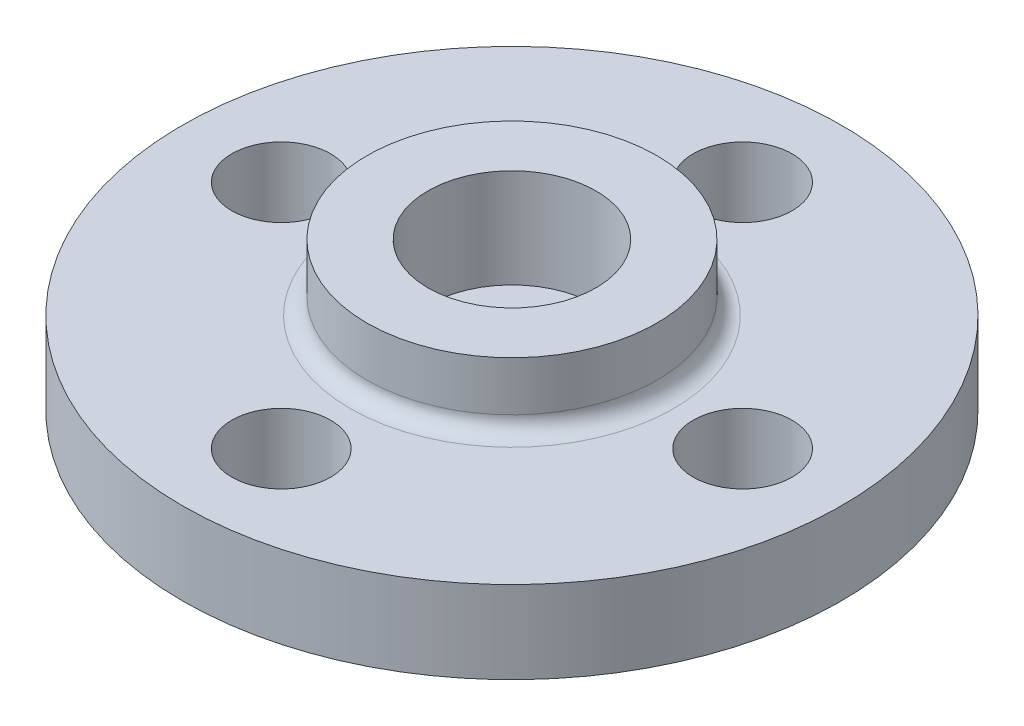
SolidWorks part; units mm, degrees
ref_plane "前视基准面" through (0, 0, 0) normal (0, 0, 1) x (1, 0, 0)
ref_plane "上视基准面" through (0, 0, 0) normal (0, 1, 0) x (1, 0, 0)
ref_plane "右视基准面" through (0, 0, 0) normal (1, 0, 0) x (0, 0, -1)
sketch "草图1" plane through (0, 0, 0) normal (0, 1, 0) x (1, 0, 0)
  circle A0 centre (0, 0) radius 10
  circle A1 centre (0, 0) radius 7 construction
  circle A2 centre (7, 0) radius 1.5
  circle A3 centre (0, 7) radius 1.5
  circle A4 centre (0, -7) radius 1.5
  circle A5 centre (-7, 0) radius 1.5
  circle A6 centre (0, 0) radius 1.5
  dimension "D1" = 14
  dimension "D2" = 20
  dimension "D3" = 3
  dimension "D4" = 3
extrude "凸台-拉伸1" add sketch "草图1" along normal blind 2.5
sketch "草图2" plane through (0, 2.5, 0) normal (0, 1, 0) x (1, 0, 0)
  circle A0 centre (0, 0) radius 4.4
  circle A1 centre (0, 0) radius 2.55
  dimension "D1" = 8.8
  dimension "D2" = 5.1
extrude "凸台-拉伸2" add sketch "草图2" along normal blind 2
fillet "圆角1" radius 0.5 1 edges at (0, 2.5, 4.4)
sketch "草图3" plane through (0, 2.5, 0) normal (0, 1, 0) x (1, 0, 0)
  circle A1 centre (0, 0) radius 2.55
  circle A2 centre (0, 0) radius 2.55
  dimension "D1" = 0
extrude "切除-拉伸1" cut sketch "草图3" against normal blind 1
